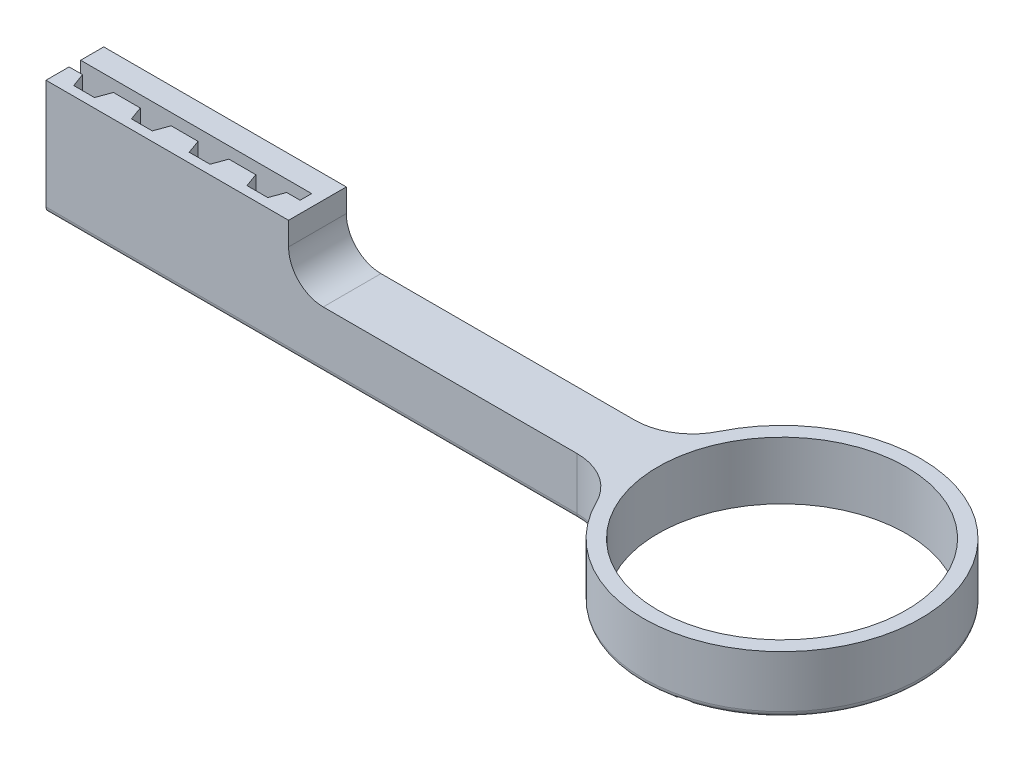
SolidWorks part; units mm, degrees
ref_plane "Спереди" through (0, 0, 0) normal (0, 0, 1) x (1, 0, 0)
ref_plane "Сверху" through (0, 0, 0) normal (0, 1, 0) x (1, 0, 0)
ref_plane "Справа" through (0, 0, 0) normal (1, 0, 0) x (0, 0, -1)
sketch "Эскиз1" plane through (0, 0, 0) normal (0, 1, 0) x (1, 0, 0)
  circle A0 centre (0, 0) radius 10.75
  circle A1 centre (0, 0) radius 12
  dimension "D1" = 21.5
  dimension "D2" = 24
extrude "ring" add sketch "Эскиз1" along normal blind 5
sketch "Эскиз2" plane through (0, 0, 0) normal (0, 1, 0) x (1, 0, 0)
  line L0 (34.0214, 0) -> (-42.1067, 0) construction
  line L2 (-11.225, 2.5) -> (-61.225, 2.5)
  line L3 (-11.225, 2.5) -> (-11.225, -2.5)
  line L4 (-11.225, -2.5) -> (-61.225, -2.5)
  line L5 (-61.225, 2.5) -> (-61.225, -2.5)
  circle A0 centre (0, 0) radius 11.5 construction
  dimension "D3" = 23
  dimension "D1" = 2.5
  dimension "D2" = 5
  dimension "D4" = 50
extrude "stick" add sketch "Эскиз2" along normal blind 5
sketch "Эскиз3" plane through (0, 0, 0) normal (0, 1, 0) x (1, 0, 0)
  line L0 (-61.225, -2.5) -> (-11.7367, -2.5) construction
  line L1 (-61.225, 2.5) -> (-40.225, 2.5)
  line L2 (-61.225, 2.5) -> (-61.225, -2.5)
  line L3 (-61.225, -2.5) -> (-40.225, -2.5)
  line L4 (-40.225, 2.5) -> (-40.225, -2.5)
  dimension "D1" = 21
extrude "key" add sketch "Эскиз3" along normal blind 10
fillet "Скругление1" radius 5 2 edges at (-11.7367, 2.5, 2.5) (-11.7367, 2.5, -2.5)
ref_plane "Плоскость1" through (0, 2.5, 0) normal (0, 1, 0) x (-1, 0, 0)
sketch "Эскиз4" plane through (0, 2.5, 0) normal (0, 1, 0) x (1, 0, 0)
  line L0 (-61.225, 0) -> (-40.225, 0) construction
  line L1 (-61.225, 2.5) -> (-61.225, -2.5) construction
  line L2 (-40.225, -2.5) -> (-40.225, 2.5) construction
  line L3 (-61.225, 0.5) -> (-41.225, 0.5)
  line L4 (-59.625, -1.7) -> (-57.825, -1.7)
  line L5 (-60.0617, -0.5) -> (-41.2194, -0.5) construction
  line L6 (-60.0617, -0.5) -> (-59.625, -1.7) construction
  line L7 (-60.0617, -0.5) -> (-59.625, -1.7)
  line L8 (-57.825, -1.7) -> (-57.3882, -0.5)
  line L9 (-58.725, 1.0157) -> (-58.725, -3.4603) construction
  line L10 (-60.0617, -0.5) -> (-61.225, -0.5)
  line L11 (-57.3882, -0.5) -> (-56.225, -0.5)
  line L12 (-61.225, 0.5) -> (-61.225, -0.5)
  line L13 (-55.0617, -0.5) -> (-56.225, -0.5)
  line L14 (-55.0617, -0.5) -> (-54.625, -1.7)
  line L15 (-54.625, -1.7) -> (-52.825, -1.7)
  line L16 (-52.825, -1.7) -> (-52.3882, -0.5)
  line L17 (-52.3882, -0.5) -> (-51.225, -0.5)
  line L18 (-50.0617, -0.5) -> (-51.225, -0.5)
  line L19 (-50.0617, -0.5) -> (-49.625, -1.7)
  line L20 (-49.625, -1.7) -> (-47.825, -1.7)
  line L21 (-47.825, -1.7) -> (-47.3882, -0.5)
  line L22 (-47.3882, -0.5) -> (-46.225, -0.5)
  line L23 (-45.0617, -0.5) -> (-46.225, -0.5)
  line L24 (-45.0617, -0.5) -> (-44.625, -1.7)
  line L25 (-44.625, -1.7) -> (-42.825, -1.7)
  line L26 (-42.825, -1.7) -> (-42.3882, -0.5)
  line L27 (-42.3882, -0.5) -> (-41.225, -0.5)
  line L28 (-41.225, 0.5) -> (-41.225, -0.5)
  point P12 (-58.725, -1.7)
  dimension "D1" = 1.8
  dimension "D2" = 0.5
  dimension "D3" = 0.5
  dimension "D4" = 1.2
  dimension "D5" = 110
  dimension "D6" = 5
  dimension "D7" = 40
fillet "Скругление5" radius 3 1 edges at (-40.225, 5, 0)
extrude "Вытянуть1" cut sketch "Эскиз4" against normal through all and the other way through all
fillet "Скругление7" radius 0.5 5 edges at (-38.2406, 0, 2.5) (-12.6132, 0, 3.2556) (-38.2406, 0, -2.5) (-12.6132, 0, -3.2556) (12, 0, 0)
